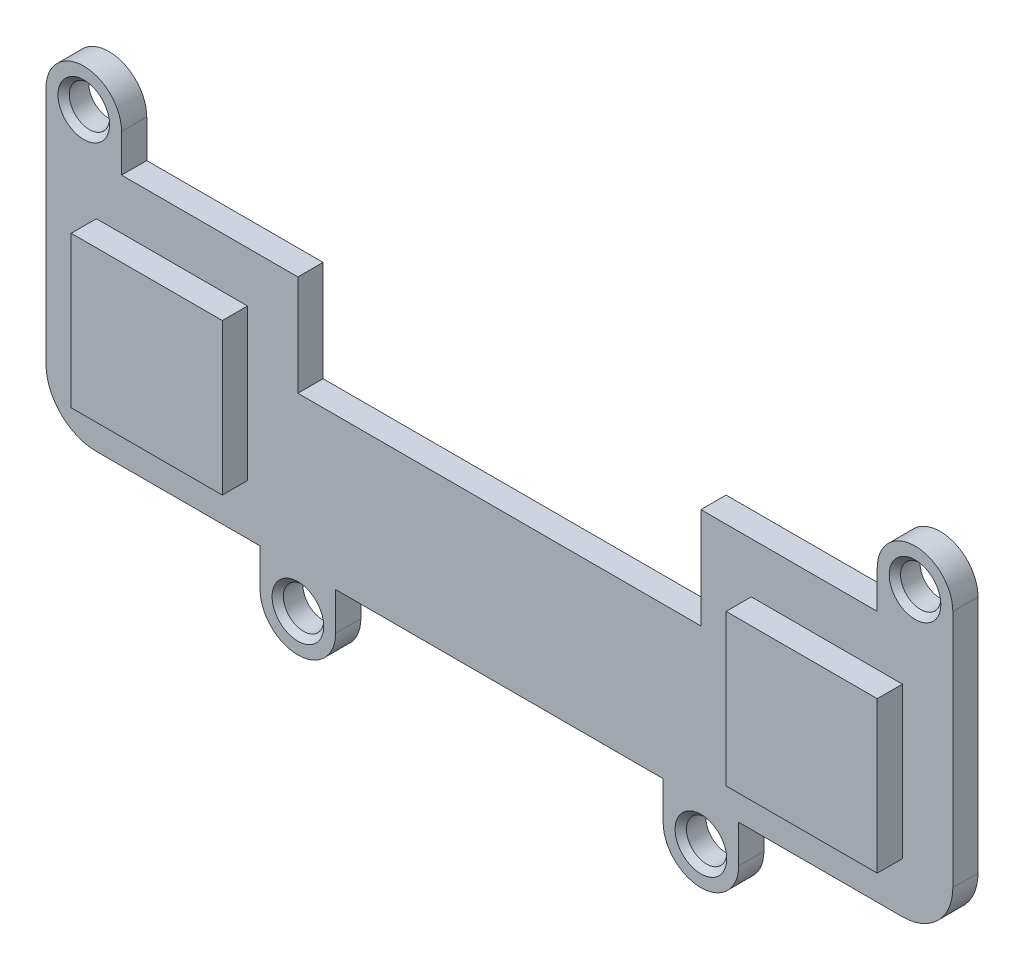
SolidWorks part; units mm, degrees
material "镁合金"
ref_plane "前视基准面" through (0, 0, 0) normal (0, 0, 1) x (1, 0, 0)
ref_plane "上视基准面" through (0, 0, 0) normal (0, 1, 0) x (1, 0, 0)
ref_plane "右视基准面" through (0, 0, 0) normal (1, 0, 0) x (0, 0, -1)
sketch "草图1" plane through (0, 0, 0) normal (0, 0, 1) x (1, 0, 0)
  line L1 (-18, 5) -> (18, 5)
  line L2 (-18, 5) -> (-18, -5)
  line L3 (-18, -5) -> (18, -5)
  line L4 (18, 5) -> (18, -5)
  line L5 (-18, 5) -> (18, -5) construction
  line L6 (-18, -5) -> (18, 5) construction
  line L7 (-8, 5) -> (8, 5)
  line L8 (-8, 5) -> (-8, 1)
  line L9 (-8, 1) -> (8, 1)
  line L10 (8, 5) -> (8, 1)
  line L11 (-18, 5) -> (-15, 5)
  line L12 (-18, 5) -> (-18, 6.5)
  line L13 (-18, 6.5) -> (-15, 6.5)
  line L14 (-15, 5) -> (-15, 6.5)
  line L15 (18, 5) -> (15, 5)
  line L16 (18, 5) -> (18, 6.5)
  line L17 (18, 6.5) -> (15, 6.5)
  line L18 (15, 5) -> (15, 6.5)
  line L19 (-9.5, -5) -> (-6.5, -5)
  line L20 (-9.5, -5) -> (-9.5, -6.5)
  line L21 (-9.5, -6.5) -> (-6.5, -6.5)
  line L22 (-6.5, -5) -> (-6.5, -6.5)
  line L23 (9.5, -5) -> (6.5, -5)
  line L24 (9.5, -5) -> (9.5, -6.5)
  line L25 (9.5, -6.5) -> (6.5, -6.5)
  line L26 (6.5, -5) -> (6.5, -6.5)
  circle A0 centre (-16.5, 6.5) radius 1.5
  circle A1 centre (16.5, 6.5) radius 1.5
  circle A2 centre (-8, -6.5) radius 1.5
  circle A3 centre (8, -6.5) radius 1.5
  point P0 (0, 0)
  point P28 (-8, -6.5)
  point P29 (8, -6.5)
  dimension "D7" = 3
  dimension "D9" = 3
  dimension "D1" = 10
  dimension "D2" = 36
  dimension "D3" = 10
  dimension "D4" = 16
  dimension "D5" = 4
  dimension "D6" = 1.5
  dimension "D8" = 1.5
  dimension "D10" = 3
  dimension "D11" = 1.5
  dimension "D12" = 1.5
  dimension "D13" = 3
extrude "凸台-拉伸1" add sketch "草图1" along normal blind 1 contours L1 L10 L9 L8 L2 L3 L4 | L21 A2 | L21 A2 | A2 L3 L20 | A2 L22 L19 | L25 A3 | L25 A3 | A3 L3 L26 | A3 L24 L23 | A0 L12 L1 | L13 A0 | A0 L11 L14 | L13 A0 | A1 L18 L1 | L17 A1 | A1 L15 L16 | L17 A1
sketch "草图2" plane through (0, 0, 1) normal (0, 0, 1) x (1, 0, 0)
  line L0 (-18, 6.5) -> (-18, -5) construction
  line L1 (-16, 3) -> (-10, 3)
  line L2 (-16, 3) -> (-16, -3)
  line L3 (-16, -3) -> (-10, -3)
  line L4 (-10, 3) -> (-10, -3)
  line L5 (10, 3) -> (16, 3)
  line L6 (10, 3) -> (10, -3)
  line L7 (10, -3) -> (16, -3)
  line L8 (16, 3) -> (16, -3)
  line L9 (-18, -5) -> (-9.5, -5) construction
  line L10 (9.5, -5) -> (18, -5) construction
  line L11 (18, 6.5) -> (18, -5) construction
  dimension "D1" = 6
  dimension "D2" = 6
  dimension "D3" = 2
  dimension "D4" = 2
  dimension "D5" = 6
  dimension "D6" = 6
  dimension "D7" = 2
  dimension "D8" = 2
extrude "凸台-拉伸2" add sketch "草图2" along normal blind 1
sketch "草图3" plane through (0, 0, 0) normal (0, 0, -1) x (-1, 0, 0)
  line L1 (-8, 1) -> (12, 1)
  line L2 (-8, 1) -> (-8, 0)
  line L3 (-8, 0) -> (12, 0)
  line L4 (12, 1) -> (12, 0)
  dimension "D1" = 20
  dimension "D2" = 1
extrude "凸台-拉伸3" add sketch "草图3" along normal blind 1.5
fillet "圆角1" radius 2 2 edges at (18, -5, 0.5) (-18, -5, 0.5)
hole_wizard "M2 螺纹孔1" positions "草图4" profile "草图5" tap size "M2" standard "GB" end condition up to next
sketch "草图4" plane through (0, 0, 1) normal (0, 0, 1) x (1, 0, 0)
  point P0 (-16.5, 6.5)
  point P3 (-8, -6.5)
  point P6 (8, -6.5)
  point P9 (16.5, 6.5)
sketch "草图5" plane through (-16.5, 6.5, 1) normal (1, 0, 0) x (0, -1, 0)
  line L0 (0, 0) -> (0, 1)
  line L1 (0, 1) -> (0.8, 1)
  line L2 (0.8, 1) -> (0.8, 0.225)
  line L3 (0.8, 0.225) -> (1.025, 0)
  line L5 (1.025, 0) -> (0, 0)
  line L6 (-0.8, 0.225) -> (-1.025, 0) construction
  line L11 (0, -6.35) -> (0, 107.95) construction
  dimension "通孔螺纹孔钻头直径" = 1.6
  dimension "通孔螺纹孔钻头深度" = 1
  dimension "近端锥形沉头孔直径" = 2.05
  dimension "近端锥形沉头孔角度" = 90
cosmetic thread "孔螺蚊线1" parameters "D2"=2
cosmetic thread "孔螺蚊线2" parameters "D2"=2
cosmetic thread "孔螺蚊线3" parameters "D2"=2
cosmetic thread "孔螺蚊线4" parameters "D2"=2
sketch "草图7" plane through (-18, 0, 0) normal (-1, 0, 0) x (0, 0, 1)
  line L0 (0, 8.5337) -> (0, -8.9478)
extrude "切除-拉伸1" cut sketch "草图7" against normal through all flip side to cut
